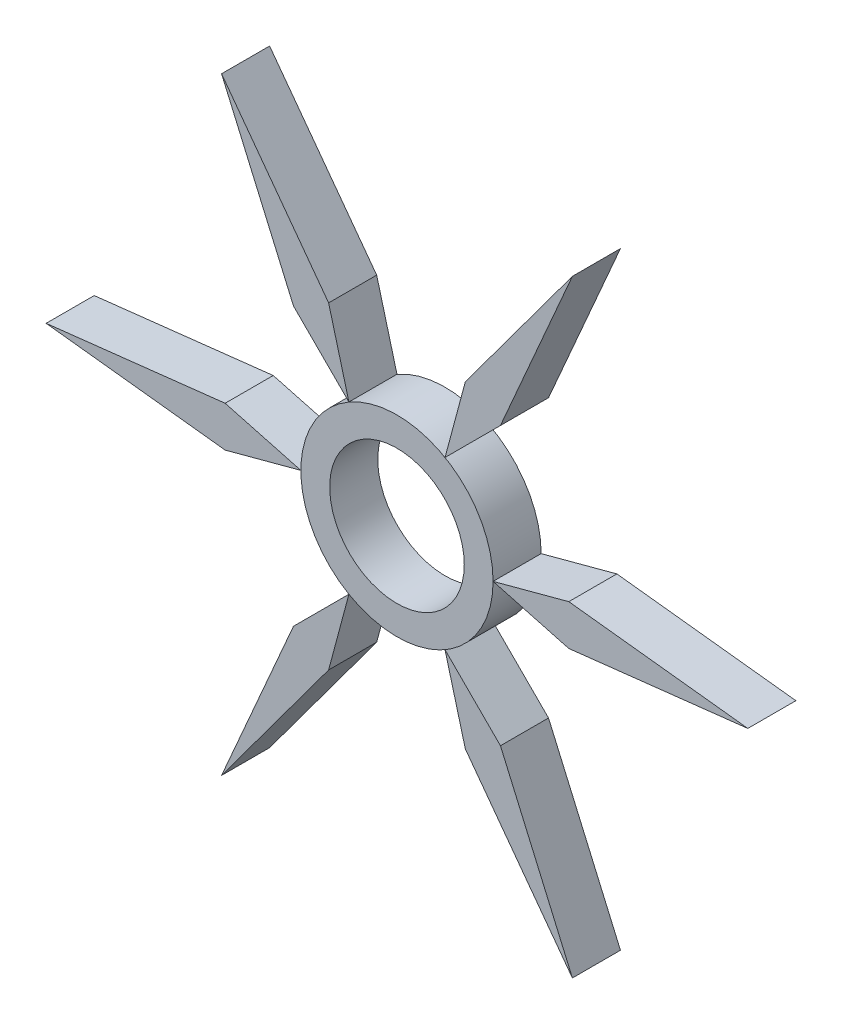
SolidWorks part; units mm, degrees
ref_plane "Front Plane" through (0, 0, 0) normal (0, 0, 1) x (1, 0, 0)
ref_plane "Top Plane" through (0, 0, 0) normal (0, 1, 0) x (1, 0, 0)
ref_plane "Right Plane" through (0, 0, 0) normal (1, 0, 0) x (0, 0, -1)
sketch "Sketch1" plane through (0, 0, 0) normal (0, 0, 1) x (1, 0, 0)
  line L0 (20, 0) -> (35.7517, 4.2207)
  line L1 (0, 0) -> (81.2575, 0) construction
  line L2 (20, 0) -> (35.7517, -4.2207)
  line L3 (35.7517, 4.2207) -> (73, 0)
  line L4 (35.7517, -4.2207) -> (73, 0)
  line L5 (14.2207, -33.0722) -> (36.5, -63.2199)
  line L6 (21.5311, -28.8516) -> (36.5, -63.2199)
  line L7 (10, -17.3205) -> (21.5311, -28.8516)
  line L8 (10, -17.3205) -> (14.2207, -33.0722)
  line L9 (-21.5311, -28.8516) -> (-36.5, -63.2199)
  line L10 (-14.2207, -33.0722) -> (-36.5, -63.2199)
  line L11 (-10, -17.3205) -> (-14.2207, -33.0722)
  line L12 (-10, -17.3205) -> (-21.5311, -28.8516)
  line L13 (-35.7517, 4.2207) -> (-73, 0)
  line L14 (-35.7517, -4.2207) -> (-73, 0)
  line L15 (-20, 0) -> (-35.7517, -4.2207)
  line L16 (-20, 0) -> (-35.7517, 4.2207)
  line L17 (-14.2207, 33.0722) -> (-36.5, 63.2199)
  line L18 (-21.5311, 28.8516) -> (-36.5, 63.2199)
  line L19 (-10, 17.3205) -> (-21.5311, 28.8516)
  line L20 (-10, 17.3205) -> (-14.2207, 33.0722)
  line L21 (21.5311, 28.8516) -> (36.5, 63.2199)
  line L22 (14.2207, 33.0722) -> (36.5, 63.2199)
  line L23 (10, 17.3205) -> (14.2207, 33.0722)
  line L24 (10, 17.3205) -> (21.5311, 28.8516)
  circle A0 centre (0, 0) radius 14
  circle A1 centre (0, 0) radius 20
  circle A2 centre (0, 0) radius 73 construction
  arc A3 (-35.7517, 4.2207) -> (-35.7517, -4.2207) centre (0, 0) ccw construction
  arc A4 (-14.2207, 33.0722) -> (-21.5311, 28.8516) centre (0, 0) ccw construction
  arc A5 (21.5311, 28.8516) -> (14.2207, 33.0722) centre (0, 0) ccw construction
  arc A6 (35.7517, -4.2207) -> (35.7517, 4.2207) centre (0, 0) ccw construction
  arc A7 (14.2207, -33.0722) -> (21.5311, -28.8516) centre (0, 0) ccw construction
  arc A8 (-21.5311, -28.8516) -> (-14.2207, -33.0722) centre (0, 0) ccw construction
  point P11 (0, 0)
  point P13 (0, 0)
  point P33 (0, 0)
  dimension "D1" = 28
  dimension "D2" = 40
  dimension "D3" = 146
  dimension "D4" = 72
  dimension "D5" = 15
extrude "Boss-Extrude1" add sketch "Sketch1" along normal mid plane 10 contours A1 A0 | L11 L12 L9 L10 | L7 L8 L5 L6 | L20 L17 L18 L19 | L13 L14 L15 L16 | L3 L4 L2 L0 | L21 L22 L23 L24
